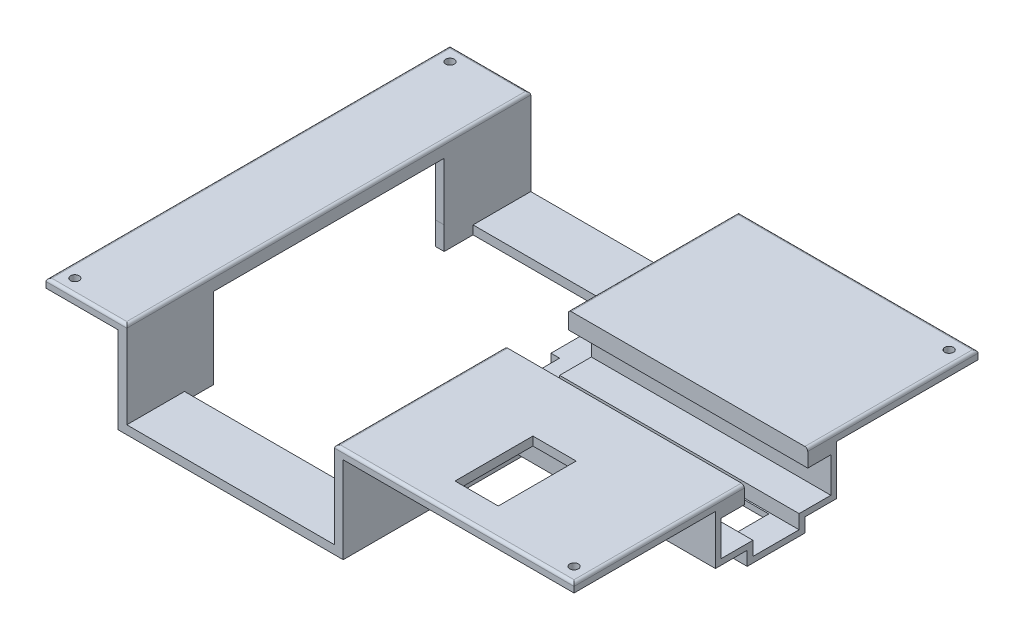
SolidWorks part; units mm, degrees
other "Markup1"
sketch "Sketch10" plane through (81.5, 3, 60) normal (0.9977, 0.0672, 0.0043) x (0.0185, -0.2123, -0.977)
ref_plane "Front Plane" through (0, 0, 0) normal (0, 0, 1) x (1, 0, 0)
ref_plane "Top Plane" through (0, 0, 0) normal (0, 1, 0) x (1, 0, 0)
ref_plane "Right Plane" through (0, 0, 0) normal (1, 0, 0) x (0, 0, -1)
sketch "Sketch1" plane through (0, 0, 0) normal (0, 1, 0) x (1, 0, 0)
  line L1 (91.5, -70) -> (-91.5, -70)
  line L2 (91.5, -70) -> (91.5, 70)
  line L3 (91.5, 70) -> (-91.5, 70)
  line L4 (-91.5, -70) -> (-91.5, 70)
  line L5 (91.5, -70) -> (-91.5, 70) construction
  line L6 (91.5, 70) -> (-91.5, -70) construction
  point P0 (0, 0)
  dimension "D1" = 183
  dimension "D2" = 140
extrude "Boss-Extrude1" add sketch "Sketch1" along normal blind 3
sketch "Sketch2" plane through (0, 0, 0) normal (0, -1, 0) x (1, 0, 0)
  line L0 (-91.5, 70) -> (91.5, 70) construction
  line L1 (-66.5, 70) -> (11.5, 70)
  line L2 (-66.5, 70) -> (-66.5, -70)
  line L3 (-66.5, -70) -> (11.5, -70)
  line L4 (11.5, 70) -> (11.5, -70)
  line L5 (91.5, -70) -> (-91.5, -70) construction
  line L6 (-91.5, -70) -> (-91.5, 70) construction
  line L7 (91.5, 70) -> (91.5, -70) construction
  dimension "D1" = 25
  dimension "D2" = 80
extrude "Boss-Extrude2" add sketch "Sketch2" along normal blind 30
sketch "Sketch3" plane through (0, 0, 70) normal (0, 0, 1) x (1, 0, 0)
  line L0 (-91.5, 3) -> (91.5, 3) construction
  line L1 (-63.5, 3) -> (8.5, 3)
  line L2 (-63.5, 3) -> (-63.5, -27)
  line L3 (-63.5, -27) -> (8.5, -27)
  line L4 (8.5, 3) -> (8.5, -27)
  line L5 (-66.5, -30) -> (-66.5, 0) construction
  line L6 (11.5, -30) -> (11.5, 0) construction
  line L7 (11.5, -30) -> (-66.5, -30) construction
  dimension "D1" = 3
  dimension "D2" = 3
  dimension "D3" = 3
extrude "Cut-Extrude1" cut sketch "Sketch3" against normal up to surface (140 mm away) up to face at (-13.75, -6.75, -70)
ref_plane "Plane1" through (8.5, 3, 70) normal (0, 1, 0) x (1, 0, 0)
sketch "Sketch5" plane through (0, 0, 0) normal (0, -1, 0) x (1, 0, 0)
  line L0 (11.5, -70) -> (11.5, 70) construction
  line L1 (11.5, 35) -> (91.5, 35)
  line L2 (11.5, 35) -> (11.5, -35)
  line L3 (11.5, -35) -> (91.5, -35)
  line L4 (91.5, 35) -> (91.5, -35)
  line L5 (91.5, 70) -> (91.5, -70) construction
  line L6 (11.5, 70) -> (91.5, 70) construction
  line L7 (91.5, -70) -> (11.5, -70) construction
  dimension "D1" = 35
  dimension "D2" = 35
extrude "Boss-Extrude3" add sketch "Sketch5" along normal blind 25
sketch "Sketch6" plane through (91.5, 0, 0) normal (1, 0, 0) x (0, 0, -1)
  line L0 (-20, 3) -> (-20, -4.6726)
  line L1 (-70, 3) -> (70, 3) construction
  line L2 (-20, -4.6726) -> (-30, -4.6726)
  line L3 (-30, -4.6726) -> (-30, -20)
  line L4 (-30, -20) -> (30, -20)
  line L5 (30, -20) -> (30, -4.6726)
  line L6 (30, -4.6726) -> (20, -4.6726)
  line L7 (20, -4.6726) -> (20, 3)
  line L8 (-35, -25) -> (-35, 0) construction
  line L9 (35, -25) -> (35, 0) construction
  line L10 (-35, -25) -> (-35, 0) construction
  line L11 (35, -25) -> (35, 0) construction
  line L12 (35, -25) -> (-35, -25) construction
  dimension "D1" = 15
  dimension "D2" = 15
  dimension "D3" = 5
  dimension "D4" = 5
  dimension "D5" = 5
extrude "Cut-Extrude2" cut sketch "Sketch6" against normal blind 85 and the other way through all
sketch "Sketch7" plane through (0, -27, 0) normal (0, 1, 0) x (1, 0, 0)
  line L0 (8.5, 70) -> (-63.5, 70) construction
  line L1 (-28.5, 25) -> (-8.5, 25)
  line L2 (-28.5, 25) -> (-28.5, -5)
  line L3 (-28.5, -5) -> (-8.5, -5)
  line L4 (-8.5, 25) -> (-8.5, -5)
  line L5 (-63.5, -70) -> (8.5, -70) construction
  line L6 (8.5, 70) -> (8.5, -70) construction
  dimension "D1" = 20
  dimension "D2" = 30
  dimension "D3" = 45
  dimension "D4" = 65
  dimension "D5" = 17
extrude "Cut-Extrude3" cut sketch "Sketch7" against normal blind 85
sketch "Sketch8" plane through (-63.5, 0, 0) normal (1, 0, 0) x (0, 0, -1)
  line L0 (70, 3) -> (-70, 3) construction
  line L1 (-20, -2) -> (40, -2)
  line L2 (-20, -2) -> (-20, -22)
  line L3 (-20, -22) -> (40, -22)
  line L4 (40, -2) -> (40, -22)
  line L5 (70, -27) -> (70, 3) construction
  line L6 (-70, 3) -> (-70, -27) construction
  dimension "D1" = 20
  dimension "D2" = 60
  dimension "D3" = 5
  dimension "D4" = 30
  dimension "D5" = 50
extrude "Cut-Extrude4" cut sketch "Sketch8" against normal blind 85
sketch "Sketch9" plane through (0, -25, 0) normal (0, -1, 0) x (1, 0, 0)
  line L0 (91.5, 35) -> (11.5, 35) construction
  line L1 (31.5, 7.5) -> (81.5, 7.5)
  line L2 (31.5, 7.5) -> (31.5, -7.5)
  line L3 (31.5, -7.5) -> (81.5, -7.5)
  line L4 (81.5, 7.5) -> (81.5, -7.5)
  line L5 (11.5, 35) -> (11.5, -35) construction
  dimension "D1" = 50
  dimension "D2" = 15
  dimension "D3" = 27.5
  dimension "D4" = 20
extrude "Cut-Extrude5" cut sketch "Sketch9" against normal blind 10
sketch "Sketch11" plane through (-63.5, 0, 0) normal (1, 0, 0) x (0, 0, -1)
  line L1 (-20, -2) -> (-40, -2)
  line L2 (-20, -2) -> (-20, -22)
  line L3 (-20, -22) -> (-40, -22)
  line L4 (-40, -2) -> (-40, -22)
  dimension "D1" = 20
  dimension "D2" = 20
extrude "Cut-Extrude6" cut sketch "Sketch11" against normal blind 10
sketch "Sketch12" plane through (0, -27, 0) normal (0, 1, 0) x (1, 0, 0)
  line L1 (-28.5, -5) -> (-8.5, -5)
  line L2 (-28.5, -5) -> (-28.5, -25)
  line L3 (-28.5, -25) -> (-8.5, -25)
  line L4 (-8.5, -5) -> (-8.5, -25)
  dimension "D1" = 20
  dimension "D2" = 20
extrude "Cut-Extrude7" cut sketch "Sketch12" against normal blind 10
ref_plane "Plane2" through (-63.5, -27, -70) normal (0, 0, 1) x (1, 0, 0)
sketch "Sketch15" plane through (0, -27, 0) normal (0, 1, 0) x (1, 0, 0)
  line L0 (-63.5, 70) -> (-63.5, -70) construction
  line L1 (-53.5, 50) -> (-11.5, 50)
  line L2 (-53.5, 50) -> (-53.5, -50)
  line L3 (-53.5, -50) -> (-11.5, -50)
  line L4 (-11.5, 50) -> (-11.5, -50)
  line L5 (8.5, 70) -> (-63.5, 70) construction
  dimension "D1" = 42
  dimension "D2" = 10
  dimension "D3" = 100
  dimension "D4" = 20
extrude "Cut-Extrude8" cut sketch "Sketch15" against normal blind 10
sketch "Sketch16" plane through (91.5, 0, 0) normal (1, 0, 0) x (0, 0, -1)
  line L0 (-70, 3) -> (-20, 3) construction
  line L1 (-32.0885, 3) -> (-19, 3)
  line L2 (-32.0885, 3) -> (-32.0885, -20)
  line L3 (-32.0885, -20) -> (-19, -20)
  line L4 (-19, 3) -> (-19, -20)
  line L5 (30, -20) -> (-30, -20) construction
  line L7 (-20, -4.6726) -> (-20, 3) construction
  dimension "D1" = 1
extrude "Boss-Extrude4" add sketch "Sketch16" against normal up to surface (83 mm away) up to face at (8.5, -8.3909, 0)
sketch "Sketch17" plane through (91.5, 0, 0) normal (1, 0, 0) x (0, 0, -1)
  line L0 (20, 3) -> (70, 3) construction
  line L1 (32.3012, 3) -> (19, 3)
  line L2 (32.3012, 3) -> (32.3012, -20.7385)
  line L3 (32.3012, -20.7385) -> (19, -20.7385)
  line L4 (19, 3) -> (19, -20.7385)
  line L5 (20, 3) -> (20, -4.6726) construction
  dimension "D1" = 1
extrude "Boss-Extrude5" add sketch "Sketch17" against normal up to surface (83 mm away) up to face at (8.5, -9.1345, -6.2)
sketch "Sketch18" plane through (0, 0, 19) normal (0, 0, -1) x (-1, 0, 0)
  line L0 (-8.5, 3) -> (-8.5, -20) construction
  line L1 (-91.5, 3) -> (-8.5, 3)
  line L2 (-91.5, 3) -> (-91.5, -3)
  line L3 (-91.5, -3) -> (-8.5, -3)
  line L4 (-8.5, 3) -> (-8.5, -3)
  dimension "D1" = 6
extrude "Boss-Extrude6" add sketch "Sketch18" along normal blind 8
sketch "Sketch19" plane through (0, 0, -19) normal (0, 0, 1) x (1, 0, 0)
  line L0 (91.5, 3) -> (91.5, -20) construction
  line L1 (8.5, 3) -> (91.5, 3)
  line L2 (8.5, 3) -> (8.5, -3)
  line L3 (8.5, -3) -> (91.5, -3)
  line L4 (91.5, 3) -> (91.5, -3)
  dimension "D1" = 6
extrude "Boss-Extrude7" add sketch "Sketch19" along normal blind 8
sketch "Sketch20" plane through (91.5, 0, 0) normal (1, 0, 0) x (0, 0, -1)
  line L0 (35, -25) -> (-35, -25) construction
  line L1 (-35, 0) -> (-21, 0)
  line L2 (-35, 0) -> (-35, -25)
  line L3 (-35, -25) -> (-21, -25)
  line L4 (-21, 0) -> (-21, -25)
  line L5 (-19, -20) -> (-19, -3) construction
  dimension "D1" = 2
extrude "Cut-Extrude9" cut sketch "Sketch20" against normal up to surface (80 mm away) up to face at (11.5, -13.75, 0)
sketch "Sketch21" plane through (91.5, 0, 0) normal (1, 0, 0) x (0, 0, -1)
  line L0 (-21, -25) -> (35, -25) construction
  line L1 (35, 0) -> (21, 0)
  line L2 (35, 0) -> (35, -25)
  line L3 (35, -25) -> (21, -25)
  line L4 (21, 0) -> (21, -25)
  line L5 (19, -3) -> (19, -20) construction
  dimension "D1" = 2
extrude "Cut-Extrude10" cut sketch "Sketch21" against normal up to surface (80 mm away) up to face at (11.5, -13.75, -3.5)
sketch "Sketch22" plane through (91.5, 0, 0) normal (1, 0, 0) x (0, 0, -1)
  line L0 (21, -25) -> (-21, -25) construction
  line L1 (-21, -25) -> (21, -25)
  line L2 (-21, -25) -> (-21, -22)
  line L3 (-21, -22) -> (21, -22)
  line L4 (21, -25) -> (21, -22)
  line L5 (-21, -25) -> (21, -25) construction
  line L6 (21, 0) -> (21, -25) construction
  line L7 (19, -20) -> (-19, -20) construction
  dimension "D1" = 2
extrude "Cut-Extrude11" cut sketch "Sketch22" against normal up to surface (80 mm away) up to face at (11.5, -13.75, 0)
sketch "Sketch23" plane through (0, -27, 0) normal (0, 1, 0) x (1, 0, 0)
  line L0 (-63.5, 70) -> (-63.5, -70) construction
  line L1 (-53.5, 50) -> (-63.5, 50)
  line L2 (-53.5, 50) -> (-53.5, -50)
  line L3 (-53.5, -50) -> (-63.5, -50)
  line L4 (-63.5, 50) -> (-63.5, -50)
extrude "Cut-Extrude12" cut sketch "Sketch23" against normal up to surface (3 mm away) up to face at (-21.25, -30, 0)
sketch "Sketch24" plane through (-63.5, 0, 0) normal (1, 0, 0) x (0, 0, -1)
  line L0 (50, -30) -> (-50, -30) construction
  line L1 (-40, -22) -> (40.0007, -22)
  line L2 (-40, -22) -> (-40, -30)
  line L3 (-40, -30) -> (40.0007, -30)
  line L4 (40.0007, -22) -> (40.0007, -30)
extrude "Cut-Extrude13" cut sketch "Sketch24" against normal up to surface (3 mm away) up to face at (-66.5, -12, 0)
sketch "Sketch25" plane through (91.5, 0, 0) normal (1, 0, 0) x (0, 0, -1)
  line L1 (-19, -20) -> (-8, -20)
  line L2 (-19, -20) -> (-19, -15.15)
  line L3 (-19, -15.15) -> (-8, -15.15)
  line L4 (-8, -20) -> (-8, -15.15)
  dimension "D1" = 4.85
  dimension "D2" = 11
extrude "Boss-Extrude9" add sketch "Sketch25" against normal up to surface (83 mm away) up to face at (8.5, -7.8333, 0)
sketch "Sketch26" plane through (91.5, 0, 0) normal (1, 0, 0) x (0, 0, -1)
  line L1 (19, -20) -> (8, -20)
  line L2 (19, -20) -> (19, -15.15)
  line L3 (19, -15.15) -> (8, -15.15)
  line L4 (8, -20) -> (8, -15.15)
  dimension "D1" = 4.85
  dimension "D2" = 11
extrude "Boss-Extrude10" add sketch "Sketch26" against normal up to surface (83 mm away) up to face at (8.5, -8.8786, 1.1429)
sketch "Sketch27" plane through (91.5, 0, 0) normal (1, 0, 0) x (0, 0, -1)
  line L0 (-8, -20) -> (-8, -15.15) construction
  line L1 (-21, -22) -> (-10, -22)
  line L2 (-21, -22) -> (-21, -17.15)
  line L3 (-21, -17.15) -> (-10, -17.15)
  line L4 (-10, -22) -> (-10, -17.15)
  line L5 (-8, -15.15) -> (-19, -15.15) construction
  dimension "D1" = 2
  dimension "D2" = 2
extrude "Cut-Extrude14" cut sketch "Sketch27" against normal up to surface (80 mm away) up to face at (11.5, -13, 0)
sketch "Sketch28" plane through (91.5, 0, 0) normal (1, 0, 0) x (0, 0, -1)
  line L0 (19, -15.15) -> (8, -15.15) construction
  line L1 (21, -22) -> (10, -22)
  line L2 (21, -22) -> (21, -17.15)
  line L3 (21, -17.15) -> (10, -17.15)
  line L4 (10, -22) -> (10, -17.15)
  line L5 (8, -15.15) -> (8, -20) construction
  dimension "D1" = 2
  dimension "D2" = 2
extrude "Cut-Extrude15" cut sketch "Sketch28" against normal up to surface (80 mm away) up to face at (11.5, -13.83, 2)
sketch "Sketch29" plane through (0, 3, 0) normal (0, 1, 0) x (1, 0, 0)
  line L0 (8.5, -70) -> (91.5, -70) construction
  line L1 (40.2418, -33) -> (55.2418, -33)
  line L2 (40.2418, -33) -> (40.2418, -60)
  line L3 (40.2418, -60) -> (55.2418, -60)
  line L4 (55.2418, -33) -> (55.2418, -60)
  dimension "D1" = 27
  dimension "D2" = 15
  dimension "D3" = 10
extrude "Cut-Extrude16" cut sketch "Sketch29" against normal blind 12
fillet "Fillet2" radius 1 10 edges at (91.5, 3, 40.5) (50, 3, -70) (50, 3, 70) (-77.5, 3, -70) (-63.5, 3, 0) (8.5, 3, -40.5) (-91.5, 3, 0) (8.5, 3, 40.5) (91.5, 3, -40.5) (-77.5, 3, 70)
sketch "Sketch30" plane through (0, 3, 0) normal (0, 1, 0) x (1, 0, 0)
  line L0 (-90.5, -69) -> (-64.5, -69) construction
  line L1 (-90.5, 69) -> (-90.5, -69) construction
  circle A0 centre (-86.5, -65) radius 1.5
  dimension "D1" = 3
  dimension "D2" = 4
  dimension "D3" = 4
extrude "Cut-Extrude17" cut sketch "Sketch30" against normal up to surface (3 mm away) up to face at (-79, 0, 0)
sketch "Sketch31" plane through (0, 3, 0) normal (0, 1, 0) x (1, 0, 0)
  line L0 (-64.5, 69) -> (-90.5, 69) construction
  line L1 (-90.5, 69) -> (-90.5, -69) construction
  circle A0 centre (-86.5, 65) radius 1.5
  dimension "D1" = 3
  dimension "D2" = 4
  dimension "D3" = 4
extrude "Cut-Extrude18" cut sketch "Sketch31" against normal up to surface (3 mm away) up to face at (-86.5, 0, 66.5)
sketch "Sketch32" plane through (0, 3, 0) normal (0, 1, 0) x (1, 0, 0)
  line L0 (90.5, 69) -> (9.5, 69) construction
  line L1 (90.5, 11) -> (90.5, 69) construction
  circle A0 centre (86.5, 65) radius 1.5
  dimension "D1" = 3
  dimension "D2" = 4
  dimension "D3" = 4
extrude "Cut-Extrude19" cut sketch "Sketch32" against normal up to surface (3 mm away) up to face at (51.5, 0, -45.5)
sketch "Sketch33" plane through (0, 3, 0) normal (0, 1, 0) x (1, 0, 0)
  line L0 (90.5, -69) -> (90.5, -11) construction
  line L2 (9.5, -69) -> (90.5, -69) construction
  circle A0 centre (86.5, -65) radius 1.5
  dimension "D1" = 3
  dimension "D2" = 4
  dimension "D3" = 4
extrude "Cut-Extrude20" cut sketch "Sketch33" against normal up to surface (3 mm away) up to face at (47.7418, 0, 46.5)
